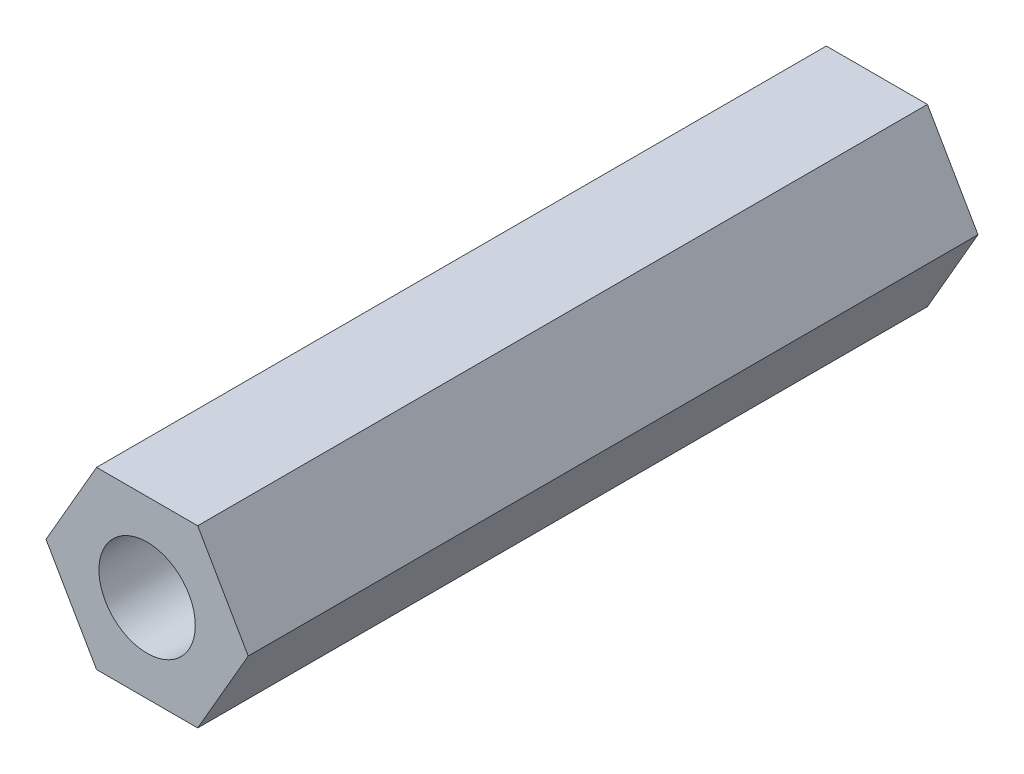
SolidWorks part; units mm, degrees
ref_plane "Front Plane" through (0, 0, 0) normal (0, 0, 1) x (1, 0, 0)
ref_plane "Top Plane" through (0, 0, 0) normal (0, 1, 0) x (1, 0, 0)
ref_plane "Right Plane" through (0, 0, 0) normal (1, 0, 0) x (0, 0, -1)
sketch "Sketch1" plane through (0, 0, 0) normal (0, 0, 1) x (1, 0, 0)
  line L1 (1.7321, 3) -> (-1.7321, 3)
  line L2 (-1.7321, 3) -> (-3.4641, 0)
  line L3 (-3.4641, 0) -> (-1.7321, -3)
  line L4 (-1.7321, -3) -> (1.7321, -3)
  line L5 (1.7321, -3) -> (3.4641, 0)
  line L6 (3.4641, 0) -> (1.7321, 3)
  circle A0 centre (0, 0) radius 3 construction
  circle A1 centre (0, 0) radius 1.65
  dimension "D2" = 3.3
  dimension "D1" = 6
extrude "Boss-Extrude1" add sketch "Sketch1" along normal blind 25
